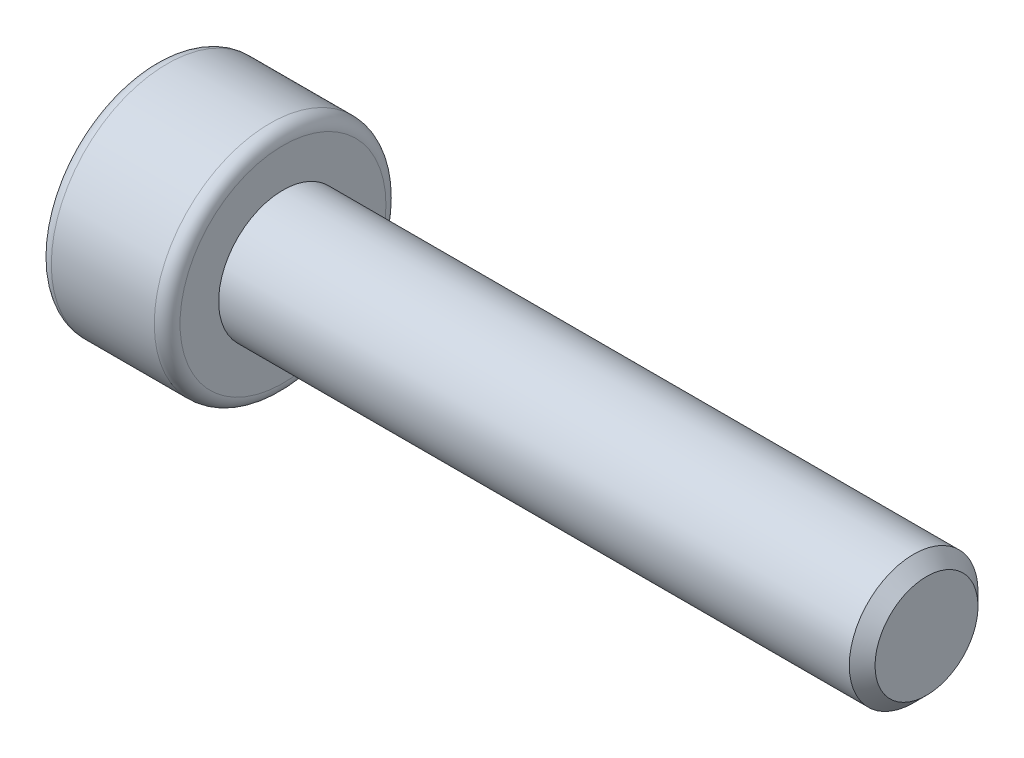
SolidWorks part; units mm, degrees
ref_plane "前视基准面" through (0, 0, 0) normal (0, 0, 1) x (1, 0, 0)
ref_plane "上视基准面" through (0, 0, 0) normal (0, 1, 0) x (1, 0, 0)
ref_plane "右视基准面" through (0, 0, 0) normal (1, 0, 0) x (0, 0, -1)
sketch "草图1" plane through (0, 0, 0) normal (0, 0, 1) x (1, 0, 0)
  line L0 (-6, 0) -> (-6, 1.8)
  line L1 (-6, 1.8) -> (-4, 1.8)
  line L2 (-4, 1.8) -> (-4, 1)
  line L3 (-4, 1) -> (6, 1)
  line L4 (6, 1) -> (6, 0)
  line L5 (6, 0) -> (-6, 0) construction
  line L6 (-6, 0) -> (6, 0)
  dimension "D1" = 3.6
  dimension "D2" = 2
  dimension "D3" = 2
  dimension "D4" = 10
revolve "旋转1" add sketch "草图1" angle 360 about L5
sketch "草图2" plane through (-6, 0, 0) normal (-1, 0, 0) x (0, 0, 1)
  line L1 (0.866, 0) -> (0.433, 0.75)
  line L2 (0.433, 0.75) -> (-0.433, 0.75)
  line L3 (-0.433, 0.75) -> (-0.866, 0)
  line L4 (-0.866, 0) -> (-0.433, -0.75)
  line L5 (-0.433, -0.75) -> (0.433, -0.75)
  line L6 (0.433, -0.75) -> (0.866, 0)
  circle A0 centre (0, 0) radius 0.75 construction
  dimension "D1" = 1.5
extrude "切除-拉伸1" cut sketch "草图2" against normal blind 1.5
fillet "圆角1" radius 0.2 2 edges at (-4, 0, -1.8) (-6, 0, -1.8)
chamfer "倒角1" distance 0.2 angle 45 1 edges at (6, 0, -1)
